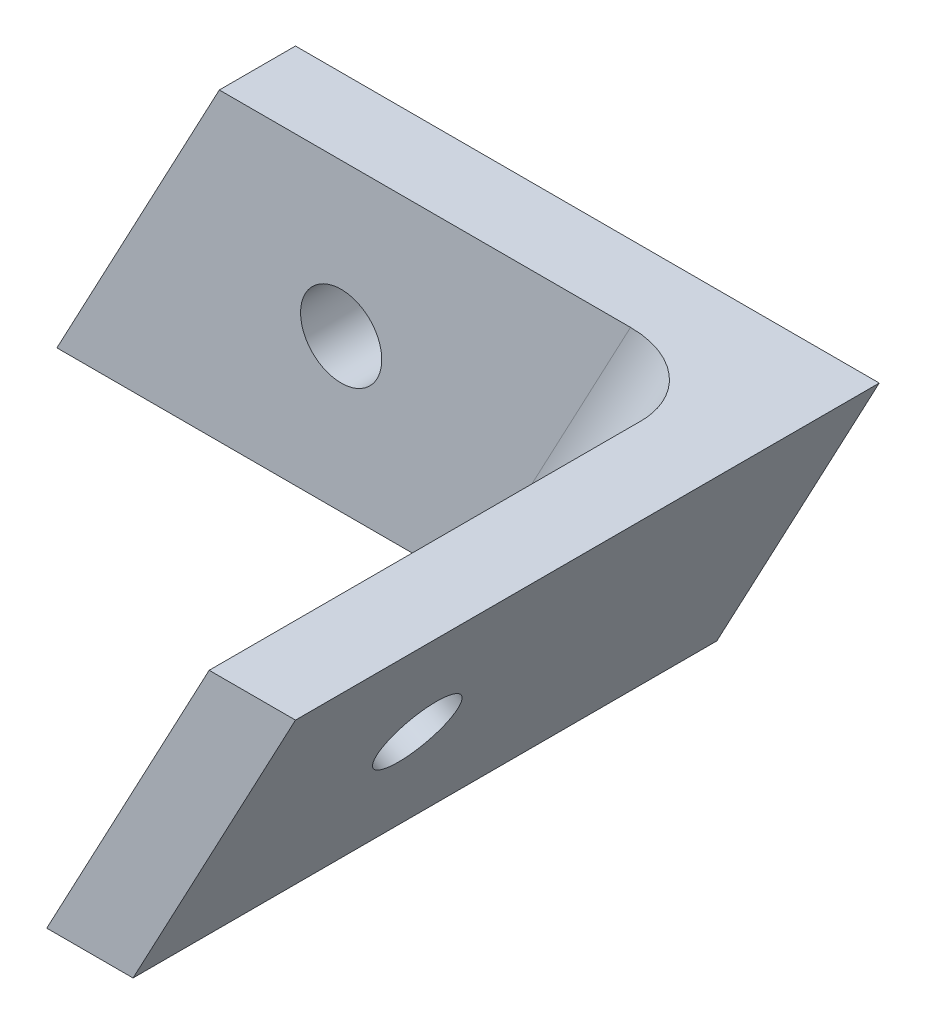
SolidWorks part; units mm, degrees
ref_plane "前视基准面" through (0, 0, 0) normal (0, 0, 1) x (1, 0, 0)
ref_plane "上视基准面" through (0, 0, 0) normal (0, 1, 0) x (1, 0, 0)
ref_plane "右视基准面" through (0, 0, 0) normal (1, 0, 0) x (0, 0, -1)
sketch "草图1" plane through (0, 0, 0) normal (0, 0, 1) x (1, 0, 0)
  line L0 (-80, 15) -> (-72, 0) construction
  line L1 (-72, 0) -> (72, 0) construction
  line L2 (72, 0) -> (80, 15) construction
  line L3 (80, 15) -> (-80, 15) construction
  line L4 (0, 15) -> (0, 0) construction
  line L5 (57, 15) -> (80, 15)
  line L6 (80, 15) -> (73.6, 3)
  line L7 (73.6, 3) -> (50.6, 3)
  line L8 (50.6, 3) -> (57, 15)
  dimension "D1" = 144
  dimension "D2" = 160
  dimension "D3" = 15
  dimension "D4" = 12
  dimension "D5" = 23
extrude "凸台-拉伸1" add sketch "草图1" along normal blind 3
sketch "草图2" plane through (0, 0, 3) normal (0, 0, 1) x (1, 0, 0)
  line L0 (76.6, 15) -> (80, 15)
  line L1 (80, 15) -> (57, 15) construction
  line L2 (73.6, 3) -> (80, 15) construction
  line L3 (80, 15) -> (73.6, 3)
  line L4 (73.6, 3) -> (70.2, 3)
  line L5 (50.6, 3) -> (73.6, 3) construction
  line L6 (70.2, 3) -> (76.6, 15)
  dimension "D1" = 3
extrude "凸台-拉伸2" add sketch "草图2" along normal blind 20
sketch "草图3" plane through (0, 0, 0) normal (0, 0, 1) x (1, 0, 0)
  line L1 (76.8, 9) -> (61.8, 9) construction
  line L3 (73.6, 3) -> (80, 15) construction
  circle A0 centre (61.8, 9) radius 1.6
  dimension "D1" = 3.2
  dimension "D2" = 15
extrude "切除-拉伸1" cut sketch "草图3" along normal up to next
sketch "草图4" plane through (56.0554, -29.8962, 0) normal (-0.8824, 0.4706, 0) x (0, 0, 1)
  line L1 (15, 44.0824) -> (0, 44.0824) construction
  line L3 (0, 37.2824) -> (0, 50.8824) construction
  circle A0 centre (15, 44.0824) radius 1.6
  dimension "D1" = 3.2
  dimension "D2" = 15
extrude "切除-拉伸2" cut sketch "草图4" along normal up to next
fillet "圆角1" radius 3 1 edges at (73.4, 9, 3)
